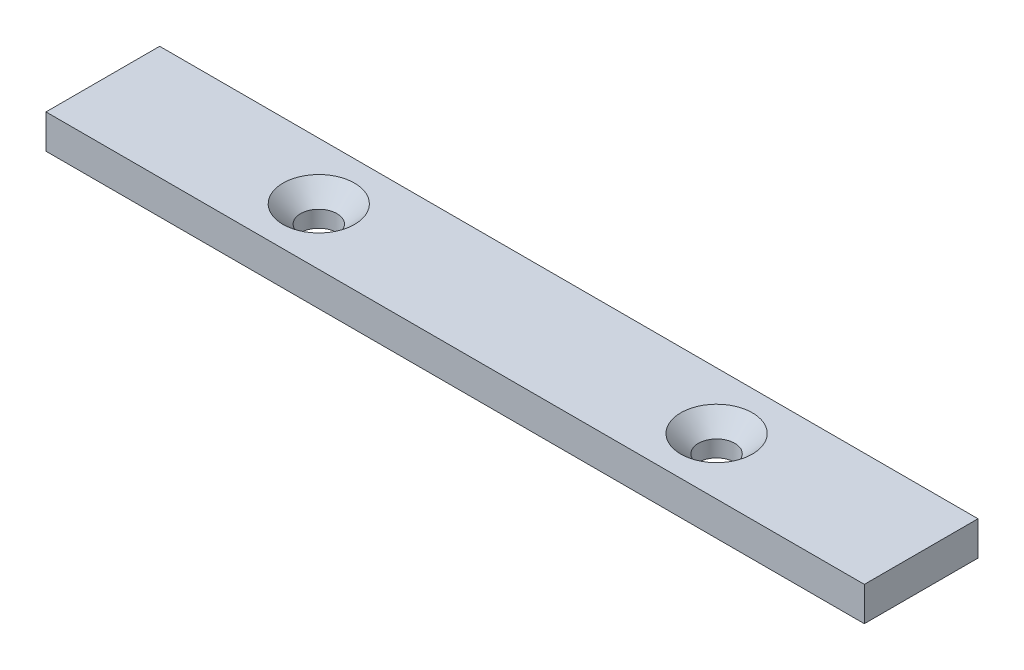
SolidWorks part; units mm, degrees
ref_plane "Front Plane" through (0, 0, 0) normal (0, 0, 1) x (1, 0, 0)
ref_plane "Top Plane" through (0, 0, 0) normal (0, 1, 0) x (1, 0, 0)
ref_plane "Right Plane" through (0, 0, 0) normal (1, 0, 0) x (0, 0, -1)
sketch "Sketch1" plane through (0, 0, 0) normal (0, 1, 0) x (1, 0, 0)
  line L1 (-72, -10) -> (72, -10)
  line L2 (-72, -10) -> (-72, 10)
  line L3 (-72, 10) -> (72, 10)
  line L4 (72, -10) -> (72, 10)
  line L5 (-72, -10) -> (72, 10) construction
  line L6 (-72, 10) -> (72, -10) construction
  point P0 (0, 0)
  dimension "D1" = 144
  dimension "D2" = 20
extrude "Boss-Extrude1" add sketch "Sketch1" along normal blind 6
hole_wizard "CSK for M6 Flat Head Machine Screw1" positions "Sketch2" profile "Sketch3" countersink size "M6" standard "ANSI Metric" end condition up to next
sketch "Sketch2" plane through (0, 6, 0) normal (0, 1, 0) x (1, 0, 0)
  line L0 (-72, 10) -> (-72, -10) construction
  line L1 (0, 0) -> (0, 10) construction
  line L2 (72, 10) -> (-72, 10) construction
  line L3 (-72, -10) -> (72, -10) construction
  point P0 (-34, 0)
  point P2 (36, 0)
  dimension "D1" = 38
  dimension "D2" = 70
sketch "Sketch3" plane through (-34, 6, 0) normal (1, 0, 0) x (0, 0, 1)
  line L0 (0, 0) -> (0, 6)
  line L1 (0, 6) -> (3.2, 6)
  line L2 (3.2, 6) -> (3.2, 3.1)
  line L3 (3.2, 3.1) -> (6.3, 0)
  line L5 (6.3, 0) -> (0, 0)
  line L6 (-3.2, 3.1) -> (-6.3, 0) construction
  line L11 (0, -6.35) -> (0, 107.95) construction
  dimension "Thru Hole Dia." = 6.4
  dimension "Thru Hole Depth" = 6
  dimension "Near C'Sink Dia." = 12.6
  dimension "Near C'Sink Angle" = 90
